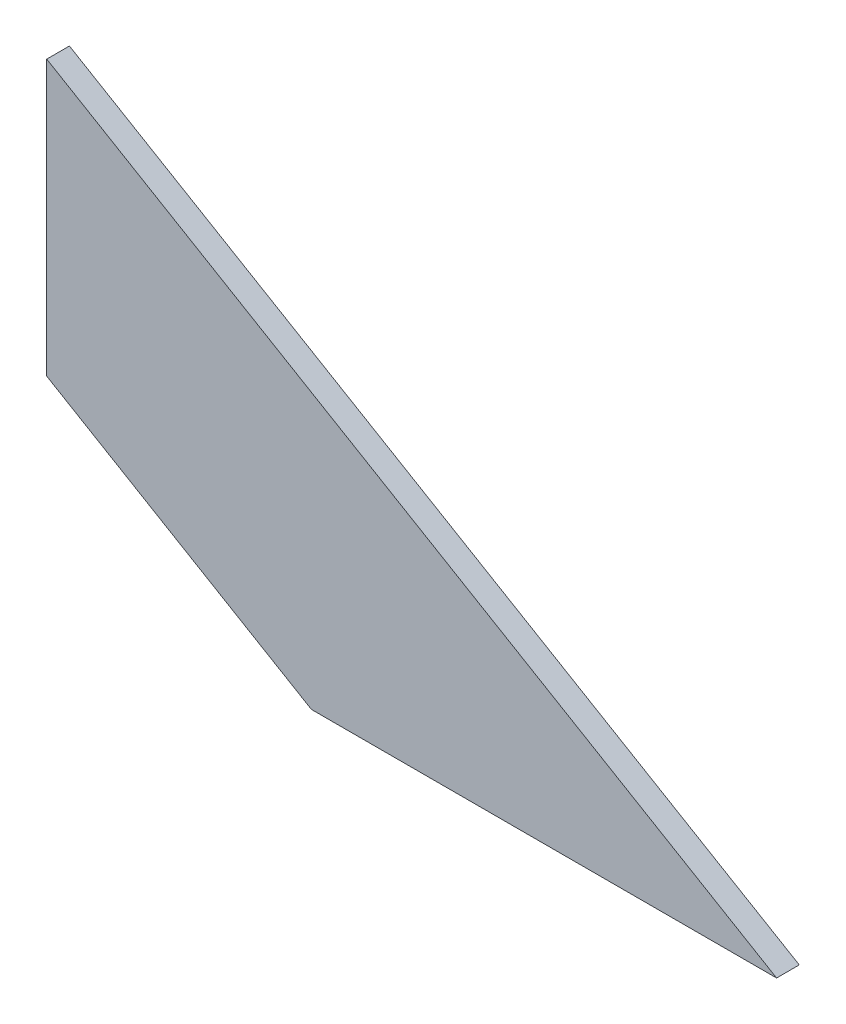
SolidWorks part; units mm, degrees
ref_plane "Front Plane" through (0, 0, 0) normal (0, 0, 1) x (1, 0, 0)
ref_plane "Top Plane" through (0, 0, 0) normal (0, 1, 0) x (1, 0, 0)
ref_plane "Right Plane" through (0, 0, 0) normal (1, 0, 0) x (0, 0, -1)
sketch "Sketch1" plane through (0, 0, 0) normal (0, 0, 1) x (1, 0, 0)
  line L1 (128.7549, 231.0461) -> (193.1232, 193.0461)
  line L3 (193.1232, 193.0461) -> (152.0983, 193.0461)
  line L5 (152.0983, 193.0461) -> (128.7549, 206.8269)
  line L7 (128.7549, 206.8269) -> (128.7549, 231.0461)
extrude "Boss-Extrude2" add sketch "Sketch1" along normal blind 2
